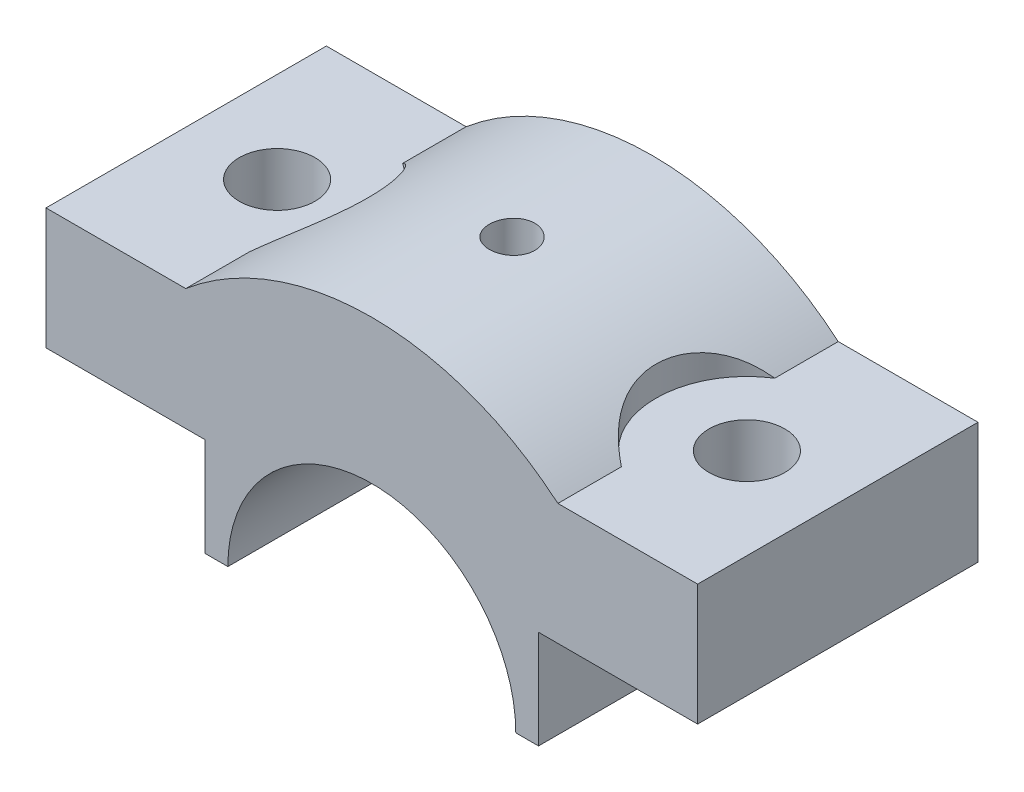
SolidWorks part; units mm, degrees
ref_plane "Front Plane" through (0, 0, 0) normal (0, 0, 1) x (1, 0, 0)
ref_plane "Top Plane" through (0, 0, 0) normal (0, 1, 0) x (1, 0, 0)
ref_plane "Right Plane" through (0, 0, 0) normal (1, 0, 0) x (0, 0, -1)
other "Center of Mass"
sketch "Sketch1" plane through (0, 0, 0) normal (0, 0, 1) x (1, 0, 0)
  line L0 (-19, 0) -> (-22, 0)
  line L1 (-22, 0) -> (-22, 13)
  line L2 (-43, 29) -> (-24.5561, 29)
  line L3 (-43, 13) -> (-43, 29)
  line L4 (-22, 13) -> (-43, 13)
  line L6 (19, 0) -> (22, 0)
  line L7 (22, 0) -> (22, 13)
  line L8 (43, 13) -> (43, 29)
  line L9 (22, 13) -> (43, 13)
  line L10 (43, 29) -> (24.5561, 29)
  arc A0 (19, 0) -> (-19, 0) centre (0, 0) ccw
  arc A1 (24.5561, 29) -> (-24.5561, 29) centre (0, 0) ccw
extrude "Boss-Extrude1" add sketch "Sketch1" along normal blind 37
sketch "Sketch3" plane through (0, 29, 0) normal (0, 1, 0) x (1, 0, 0)
  circle A0 centre (-31, -18.5) radius 5
  circle A1 centre (31, -18.5) radius 5
extrude "Cut-Extrude1" cut sketch "Sketch3" against normal blind 37
sketch "Sketch4" plane through (0, 29, 0) normal (0, 1, 0) x (1, 0, 0)
  circle A0 centre (-31, -18.5) radius 12
  circle A1 centre (31, -18.5) radius 12
extrude "Cut-Extrude2" cut sketch "Sketch4" along normal blind 12
sketch "Sketch5" plane through (0, 0, 0) normal (0, 1, 0) x (1, 0, 0)
  circle A0 centre (0, -18.5) radius 2
extrude "Cut-Extrude3" cut sketch "Sketch5" along normal blind 50
ref_plane "Plane1" through (0, 25, 0) normal (0, 1, 0) x (1, 0, 0)
sketch "Sketch6" plane through (0, 25, 0) normal (0, 1, 0) x (1, 0, 0)
  circle A0 centre (0, -18.5) radius 3
extrude "Cut-Extrude4" cut sketch "Sketch6" along normal blind 29
